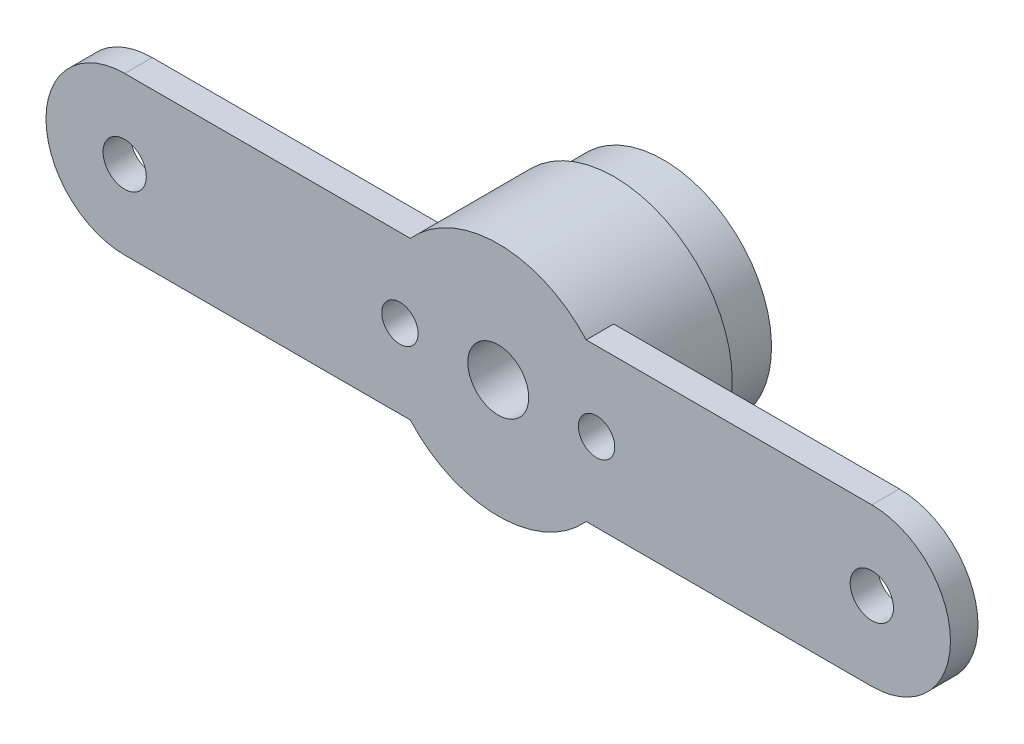
SolidWorks part; units mm, degrees
ref_plane "前视基准面" through (0, 0, 0) normal (0, 0, 1) x (1, 0, 0)
ref_plane "上视基准面" through (0, 0, 0) normal (0, 1, 0) x (1, 0, 0)
ref_plane "右视基准面" through (0, 0, 0) normal (1, 0, 0) x (0, 0, -1)
sketch "草图1" plane through (0, 0, 0) normal (0, 0, 1) x (1, 0, 0)
  line L0 (4.4721, 4) -> (19, 4)
  line L1 (-19, -4) -> (-4.4721, -4)
  line L2 (4.4721, -4) -> (19, -4)
  line L3 (-19, 4) -> (-4.4721, 4)
  circle A0 centre (0, 0) radius 1.55
  circle A1 centre (19, 0) radius 1.1
  circle A2 centre (-19, 0) radius 1.1
  arc A3 (-19, 4) -> (-19, -4) centre (-19, 0) ccw
  arc A4 (19, -4) -> (19, 4) centre (19, 0) ccw
  arc A5 (-4.4721, -4) -> (4.4721, -4) centre (0, 0) ccw
  arc A6 (4.4721, 4) -> (-4.4721, 4) centre (0, 0) ccw
  dimension "D3" = 2.2
  dimension "D4" = 2.2
  dimension "D5" = 3.1
  dimension "D7" = 8
  dimension "D9" = 4
  dimension "D6" = 8
  dimension "D1" = 19
  dimension "D2" = 19
  dimension "D10" = 4
extrude "凸台-拉伸1" add sketch "草图1" along normal blind 1.4
sketch "草图2" plane through (0, 0, 0) normal (0, 0, -1) x (-1, 0, 0)
  circle A0 centre (0, 0) radius 6
extrude "凸台-拉伸2" add sketch "草图2" along normal blind 4.5
sketch "草图3" plane through (0, 0, -4.5) normal (0, 0, -1) x (-1, 0, 0)
  circle A0 centre (0, 0) radius 5.5
  dimension "D1" = 11
extrude "凸台-拉伸3" add sketch "草图3" along normal blind 2.5
sketch "草图4" plane through (0, 0, -7) normal (0, 0, -1) x (-1, 0, 0)
  circle A0 centre (0, 0) radius 2.6
  dimension "D1" = 5.2
sketch "草图5" plane through (0, 0, -7) normal (0, 0, -1) x (-1, 0, 0)
  circle A0 centre (0, 2.6) radius 0.4
  circle A1 centre (0, 0) radius 2.6 construction
  dimension "D1" = 0.8
extrude "切除-拉伸1" cut sketch "草图5" against normal blind 5
pattern_circular "阵列(圆周)2" count 25 over 360 about axis through (0, 0, 0) along (0, 0, 1) of "切除-拉伸1"
extrude "切除-拉伸2" cut sketch "草图4" against normal blind 5
sketch "草图6" plane through (0, 0, 1.4) normal (0, 0, 1) x (1, 0, 0)
  circle A0 centre (0, 0) radius 1.55
extrude "切除-拉伸3" cut sketch "草图6" against normal blind 30
sketch "草图7" plane through (0, 0, 1.4) normal (0, 0, 1) x (1, 0, 0)
  circle A0 centre (5, 0) radius 0.925
  circle A1 centre (-5, 0) radius 0.925
  dimension "D3" = 1.85
  dimension "D4" = 1.85
  dimension "D1" = 5
  dimension "D2" = 5
extrude "切除-拉伸4" cut sketch "草图7" against normal blind 6
ref_plane "基准面1" through (6, 0, 0) normal (1, 0, 0) x (0, 0, -1)
sketch "草图8" plane through (6, 0, 0) normal (1, 0, 0) x (0, 0, -1)
  line L0 (1.6, 2.1) -> (0, 2.1)
  line L1 (1.6, 2.1) -> (1.6, -2.1)
  line L2 (0, 2.1) -> (0, -2.1)
  line L3 (1.6, -2.1) -> (0, -2.1)
  line L4 (1.6, 2.1) -> (0, -2.1) construction
  line L5 (0, 2.1) -> (1.6, -2.1) construction
  point P1 (0.8, 0)
  dimension "D1" = 4.2
  dimension "D2" = 1.6
extrude "切除-拉伸5" cut sketch "草图8" against normal blind 3.2
ref_plane "基准面2" through (-6, 0, 0) normal (-1, 0, 0) x (0, 0, 1)
sketch "草图9" plane through (-6, 0, 0) normal (-1, 0, 0) x (0, 0, 1)
  line L0 (-1.6, -2.1) -> (0, -2.1)
  line L1 (-1.6, -2.1) -> (-1.6, 2.1)
  line L2 (0, -2.1) -> (0, 2.1)
  line L3 (-1.6, 2.1) -> (0, 2.1)
  line L4 (-1.6, -2.1) -> (0, 2.1) construction
  line L5 (0, -2.1) -> (-1.6, 2.1) construction
  point P1 (-0.8, 0)
  dimension "D1" = 1.6
  dimension "D2" = 4.2
extrude "切除-拉伸6" cut sketch "草图9" against normal blind 3.2
